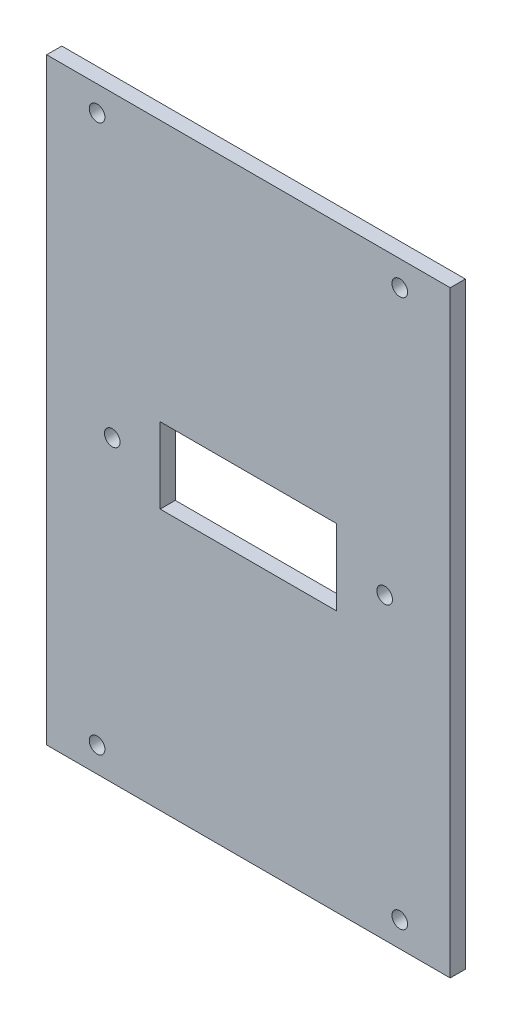
SolidWorks part; units mm, degrees
ref_plane "前视基准面" through (0, 0, 0) normal (0, 0, 1) x (1, 0, 0)
ref_plane "上视基准面" through (0, 0, 0) normal (0, 1, 0) x (1, 0, 0)
ref_plane "右视基准面" through (0, 0, 0) normal (1, 0, 0) x (0, 0, -1)
other "Configuration Table"
sketch "草图1" plane through (0, 0, 0) normal (0, 0, 1) x (1, 0, 0)
  line L0 (40, 118.5) -> (40, 95.3823) construction
  line L1 (0, 0) -> (80, 0)
  line L2 (0, 0) -> (0, 118.5)
  line L3 (0, 118.5) -> (80, 118.5)
  line L4 (80, 0) -> (80, 118.5)
  line L5 (80, 59.25) -> (41.8551, 59.25) construction
  line L7 (22.5, 66.75) -> (57.5, 66.75)
  line L8 (22.5, 66.75) -> (22.5, 51.75)
  line L9 (22.5, 51.75) -> (57.5, 51.75)
  line L10 (57.5, 66.75) -> (57.5, 51.75)
  line L11 (22.5, 66.75) -> (57.5, 51.75) construction
  line L12 (22.5, 51.75) -> (57.5, 66.75) construction
  point P9 (40, 59.25)
  point P10 (40, 59.25)
  dimension "D1" = 118.5
  dimension "D2" = 80
  dimension "D3" = 15
  dimension "D4" = 35
extrude "凸台-拉伸1" add sketch "草图1" along normal blind 3
sketch "草图2" plane through (0, 0, 3) normal (0, 0, 1) x (1, 0, 0)
  line L0 (0, 59.25) -> (80, 59.25) construction
  line L1 (0, 118.5) -> (0, 0) construction
  line L2 (80, 0) -> (80, 118.5) construction
  line L3 (40, 59.25) -> (40, 66.75) construction
  line L4 (57.5, 66.75) -> (22.5, 66.75) construction
  circle A0 centre (40, 77.25) radius 1.55
  circle A1 centre (40, 41.25) radius 1.55
  dimension "D1" = 3.1
  dimension "D2" = 18
extrude "切除-拉伸1" [suppressed] cut sketch "草图2" against normal up to next
sketch "草图3" plane through (0, 0, 3) normal (0, 0, 1) x (1, 0, 0)
  line L0 (40, 118.5) -> (40, 140.159)
  line L1 (80, 118.5) -> (0, 118.5) construction
  line L2 (22.5, 59.25) -> (37.5505, 59.25) construction
  line L3 (22.5, 66.75) -> (22.5, 51.75) construction
  circle A0 centre (10, 113.5) radius 1.55
  circle A1 centre (70, 113.5) radius 1.55
  circle A2 centre (70, 5) radius 1.55
  circle A3 centre (10, 5) radius 1.55
  dimension "D2" = 3.1
  dimension "D1" = 30
  dimension "D3" = 5
extrude "切除-拉伸2" cut sketch "草图3" against normal up to next contours A0 | A1 | A2 | A3
sketch "草图4" plane through (0, 0, 0) normal (0, 0, -1) x (-1, 0, 0)
  line L1 (-57.5, 51.75) -> (-57.5, 66.75) construction
  line L2 (0, 0) -> (-80, 0) construction
  line L3 (-40, 66.75) -> (-40, 51.75) construction
  line L4 (-57.5, 66.75) -> (-22.5, 66.75) construction
  line L5 (-22.5, 51.75) -> (-57.5, 51.75) construction
  line L6 (-57.5, 59.25) -> (-40, 59.25) construction
  circle A0 centre (-67, 59.25) radius 1.55
  circle A2 centre (-13, 59.25) radius 1.55
  dimension "D1" = 3.1
  dimension "D2" = 9.5
  dimension "D3" = 59.25
extrude "切除-拉伸3" cut sketch "草图4" against normal up to next
